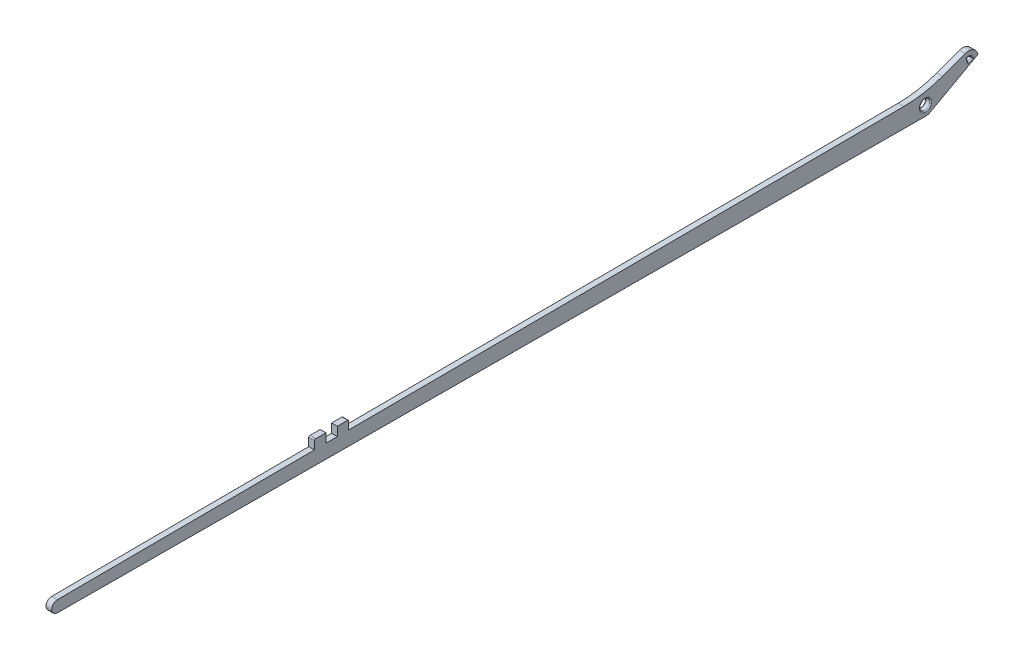
SolidWorks part; units mm, degrees
ref_plane "Спереди" through (0, 0, 0) normal (0, 0, 1) x (1, 0, 0)
ref_plane "Сверху" through (0, 0, 0) normal (0, 1, 0) x (1, 0, 0)
ref_plane "Справа" through (0, 0, 0) normal (1, 0, 0) x (0, 0, -1)
other "Configuration Table"
sketch "Эскиз1" plane through (0, 0, 0) normal (1, 0, 0) x (0, 0, -1)
  line L0 (0, 0) -> (-380, 0) construction
  line L1 (0, 0) -> (18.7939, 6.8404) construction
  line L2 (0, 0) -> (-260, 0) construction
  line L3 (17.3403, 10.8341) -> (20.2474, 2.8467)
  line L4 (-1.4536, 3.9937) -> (17.3403, 10.8341)
  line L5 (2.0466, -3.7248) -> (20.607, 6.4731)
  line L6 (-380, -2.5) -> (-380, 2.5)
  line L7 (-380, 2.5) -> (-0.0196, 4.25)
  line L8 (-380, -2.5) -> (-0.0196, -4.25)
  line L9 (-262.5, 0) -> (-257.5, 0)
  line L10 (-267.5, 0) -> (-252.5, 0)
  line L11 (-262.5, 0) -> (-262.5, 7)
  line L12 (-262.5, 7) -> (-267.5, 7)
  line L13 (-267.5, 7) -> (-267.5, 0)
  line L14 (-257.5, 0) -> (-257.5, 7)
  line L15 (-257.5, 7) -> (-252.5, 7)
  line L16 (-252.5, 7) -> (-252.5, 0)
  line L17 (20.5323, 7.4731) -> (18.7939, 6.8404)
  line L18 (20.607, 6.4731) -> (22.9438, 7.7571)
  circle A0 centre (0, 0) radius 4.25
  circle A1 centre (0, 0) radius 2.25
  arc A2 (20.2474, 2.8467) -> (17.3403, 10.8341) centre (18.7939, 6.8404) ccw
  arc A3 (19.4266, 5.102) -> (18.1611, 8.5788) centre (18.7939, 6.8404) ccw
  circle A5 centre (-380, 0) radius 2.5
  arc A6 (-9.4565, 4.2065) -> (7.4143, 7.2213) centre (-9.6867, 54.206) ccw
  point P10 (18.7939, 6.8404)
  point P17 (-380, 0)
  point P18 (-380, 0)
  point P22 (-260, 0)
  point P25 (-260, 0)
  dimension "D5" = 2
  dimension "D6" = 4.5
  dimension "D7" = 2.4
  dimension "D12" = 100
  dimension "D1" = 160
  dimension "D2" = 20
  dimension "D3" = 380
  dimension "D4" = 260
  dimension "D8" = 5
  dimension "D9" = 15
  dimension "D10" = 7
  dimension "D11" = 5
  dimension "D13" = 1
extrude "Бобышка-Вытянуть1" add sketch "Эскиз1" along normal blind 2.5
fillet "Скругление1" radius 0.5 10 edges at (1.25, 7, 267.5) (1.25, 7, 252.5) (2.5, 0, -2.25) (0, 0, -2.25) (0, 8.5171, -19.5757) (2.5, 8.5171, -19.5757) (0, 7.1568, -19.6631) (2.5, 7.1568, -19.6631) (0, 7.7096, -18.4775) (2.5, 7.7096, -18.4775)
